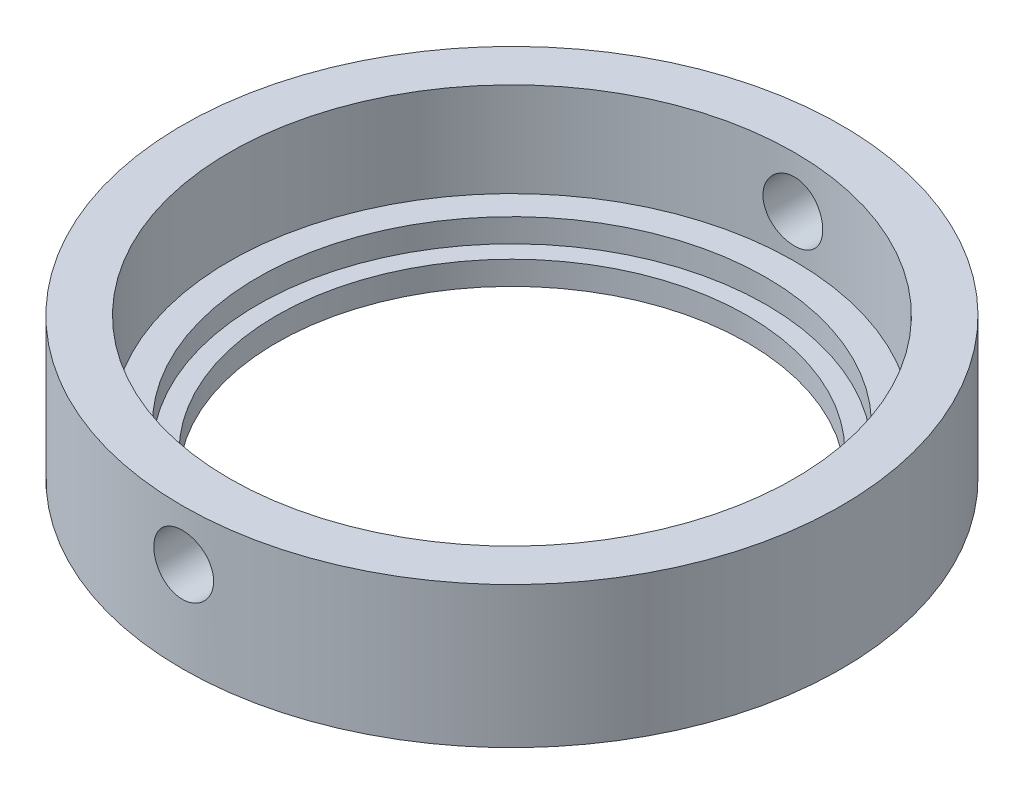
SolidWorks part; units mm, degrees
ref_plane "Front Plane" through (0, 0, 0) normal (0, 0, 1) x (1, 0, 0)
ref_plane "Top Plane" through (0, 0, 0) normal (0, 1, 0) x (1, 0, 0)
ref_plane "Right Plane" through (0, 0, 0) normal (1, 0, 0) x (0, 0, -1)
sketch "Sketch1" plane through (0, 0, 0) normal (0, 1, 0) x (1, 0, 0)
  circle A0 centre (0, 0) radius 35
  dimension "D1" = 70
extrude "Boss-Extrude1" add sketch "Sketch1" along normal blind 25
sketch "Sketch2" plane through (0, 25, 0) normal (0, 1, 0) x (1, 0, 0)
  circle A0 centre (0, 0) radius 30
  dimension "D1" = 60
extrude "Cut-Extrude1" cut sketch "Sketch2" against normal blind 20
sketch "Sketch3" plane through (0, 0, 0) normal (0, -1, 0) x (1, 0, 0)
  circle A0 centre (0, 0) radius 25
  dimension "D1" = 50
extrude "Cut-Extrude2" cut sketch "Sketch3" against normal blind 20
sketch "Sketch4" plane through (0, 5, 0) normal (0, 1, 0) x (1, 0, 0)
  circle A2 centre (0, 0) radius 27
  circle A3 centre (0, 0) radius 27
  dimension "D1" = 2
extrude "Cut-Extrude3" cut sketch "Sketch4" against normal blind 2.5
sketch "Sketch5" plane through (0, 25, 0) normal (0, 1, 0) x (1, 0, 0)
  circle A0 centre (0, 0) radius 55.9102
extrude "Cut-Extrude4" cut sketch "Sketch5" against normal blind 10
sketch "Sketch7" plane through (0, 0, 0) normal (0, 0, 1) x (1, 0, 0)
  line L0 (27, 5) -> (-27, 5) construction
  circle A0 centre (0, 9.572) radius 3.175
  dimension "D1" = 6.35
  dimension "D2" = 4.572
extrude "Cut-Extrude6" cut sketch "Sketch7" against normal through all both and the other way through all
